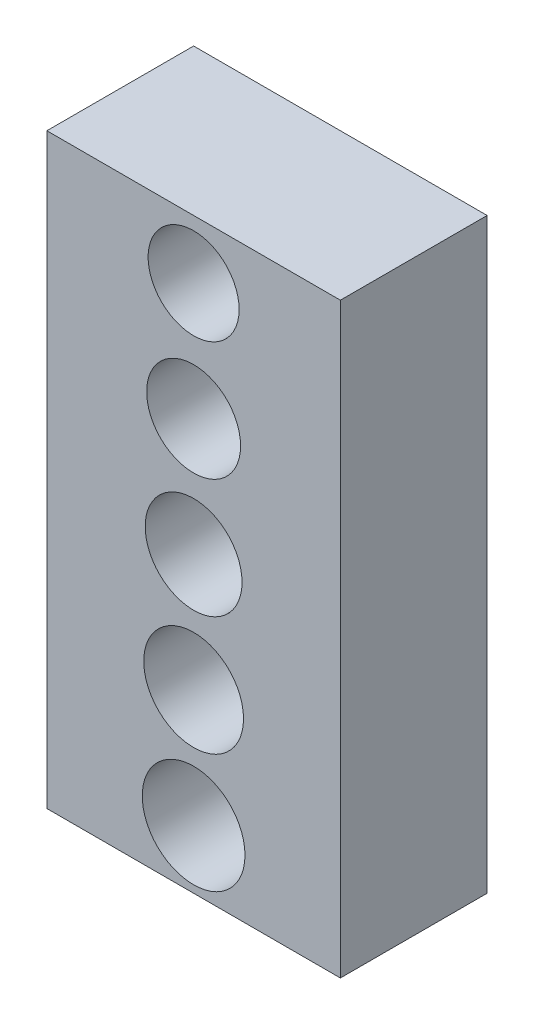
SolidWorks part; units mm, degrees
ref_plane "正面" through (0, 0, 0) normal (0, 0, 1) x (1, 0, 0)
ref_plane "平面" through (0, 0, 0) normal (0, 1, 0) x (1, 0, 0)
ref_plane "右側面" through (0, 0, 0) normal (1, 0, 0) x (0, 0, -1)
sketch "ｽｹｯﾁ1" plane through (0, 0, 0) normal (0, 0, 1) x (1, 0, 0)
  line L0 (0, 10) -> (0, -10) construction
  line L1 (5, 10) -> (-5, 10)
  line L2 (5, 10) -> (5, -10)
  line L3 (5, -10) -> (-5, -10)
  line L4 (-5, 10) -> (-5, -10)
  line L5 (5, 10) -> (-5, -10) construction
  line L6 (5, -10) -> (-5, 10) construction
  circle A0 centre (0, 8) radius 1.55
  circle A1 centre (0, -8) radius 1.75
  circle A2 centre (0, 0) radius 1.65
  circle A3 centre (0, -4) radius 1.7
  circle A4 centre (0, 4) radius 1.6
  point P0 (0, 0)
  dimension "D3" = 3.1
  dimension "D4" = 3.5
  dimension "D5" = 3.3
  dimension "D6" = 3.4
  dimension "D8" = 4
  dimension "D9" = 4
  dimension "D10" = 3.2
  dimension "D11" = 4
  dimension "D12" = 4
  dimension "D1" = 10
  dimension "D2" = 20
  dimension "D7" = 2
extrude "ﾎﾞｽ - 押し出し1" add sketch "ｽｹｯﾁ1" along normal blind 5
